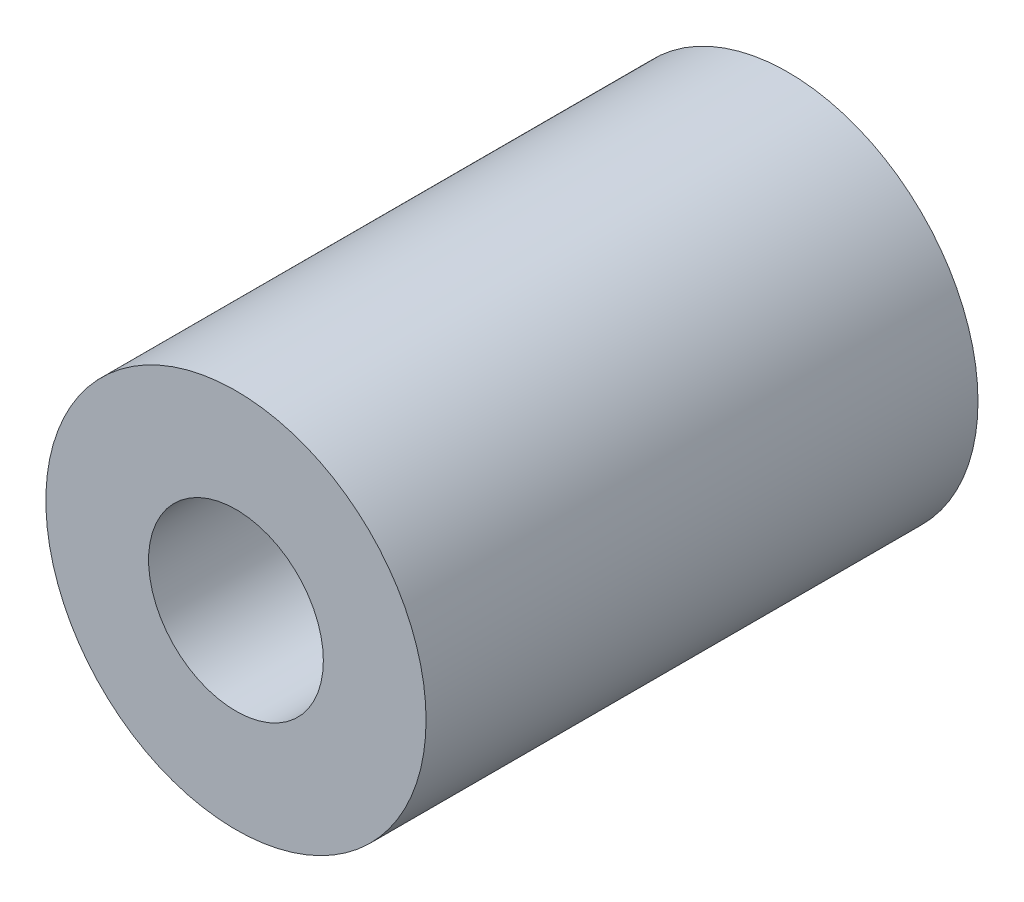
SolidWorks part; units mm, degrees
ref_plane "Front Plane" through (0, 0, 0) normal (0, 0, 1) x (1, 0, 0)
ref_plane "Top Plane" through (0, 0, 0) normal (0, 1, 0) x (1, 0, 0)
ref_plane "Right Plane" through (0, 0, 0) normal (1, 0, 0) x (0, 0, -1)
sketch "Sketch1" plane through (0, 0, 0) normal (0, 0, 1) x (1, 0, 0)
  circle A0 centre (0, 0) radius 3.1
  circle A1 centre (0, 0) radius 1.425
  dimension "D1" = 2.85
  dimension "D3" = 6.2
extrude "Boss-Extrude1" add sketch "Sketch1" along normal blind 9
